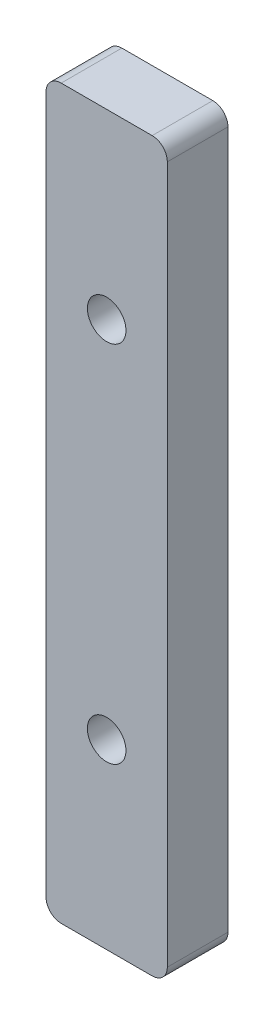
SolidWorks part; units mm, degrees
material "6061 Alloy"
ref_plane "Front Plane" through (0, 0, 0) normal (0, 0, 1) x (1, 0, 0)
ref_plane "Top Plane" through (0, 0, 0) normal (0, 1, 0) x (1, 0, 0)
ref_plane "Right Plane" through (0, 0, 0) normal (1, 0, 0) x (0, 0, -1)
sketch "Sketch1" plane through (0, 0, 0) normal (0, 0, 1) x (1, 0, 0)
  line L0 (-6.35, 38.1) -> (11.8452, 38.1) construction
  line L1 (-6.35, 0) -> (6.35, 0)
  line L2 (-6.35, 0) -> (-6.35, 76.2)
  line L3 (-6.35, 76.2) -> (6.35, 76.2)
  line L4 (6.35, 0) -> (6.35, 76.2)
  circle A0 centre (0, 57.15) radius 2.4257 construction
  circle A1 centre (0, 19.05) radius 2.4257 construction
  point P9 (0, 0)
  dimension "D4" = 4.8514
  dimension "D1" = 12.7
  dimension "D2" = 76.2
  dimension "D3" = 19.05
extrude "Extrude1" add sketch "Sketch1" against normal blind 6.35
hole_wizard "#10-32 Tapped Hole1" positions "Sketch4" profile "Sketch3" tap size "#10-32" standard "Ansi Inch"
sketch "Sketch4" plane through (0, 0, 0) normal (0, 0, 1) x (1, 0, 0)
  point P0 (0, 57.15)
  point P1 (0, 19.05)
sketch "Sketch3" plane through (0, 57.15, 0) normal (1, 0, 0) x (0, -1, 0)
  line L0 (0, 0) -> (0, 14.9293)
  line L1 (0, 14.9293) -> (2.0193, 13.716)
  line L2 (2.0193, 13.716) -> (2.0193, 0)
  line L5 (2.0193, 0) -> (0, 0)
  line L10 (0, 14.9293) -> (-2.0193, 13.716) construction
  line L11 (0, -6.35) -> (0, 107.95) construction
  dimension "Tap Drill Dia." = 4.0386
  dimension "Tap Drill Depth" = 13.716
  dimension "Drill Angle" = 118
cosmetic thread "Hole Thread1" parameters "D1"=9.652, "D2"=4.826
cosmetic thread "Hole Thread2" parameters "D1"=9.652, "D2"=4.826
fillet "Fillet1" radius 1.5875 4 edges at (6.35, 76.2, -3.175) (6.35, 0, -3.175) (-6.35, 76.2, -3.175) (-6.35, 0, -3.175)
